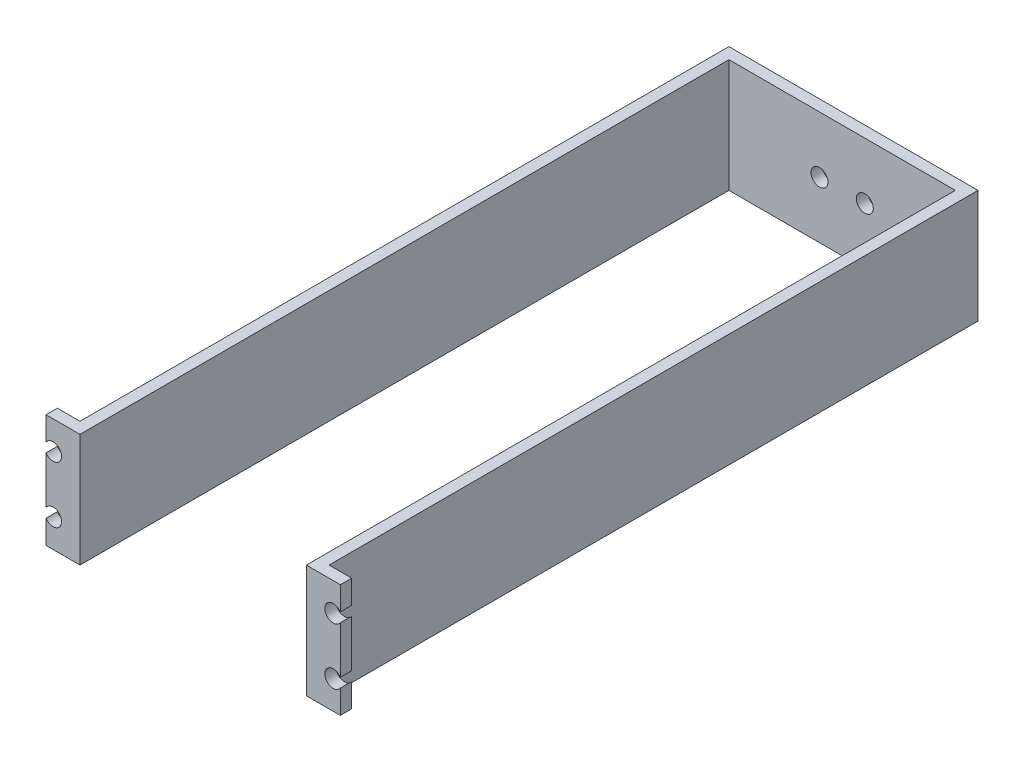
SolidWorks part; units mm, degrees
ref_plane "Plan de face" through (0, 0, 0) normal (0, 0, 1) x (1, 0, 0)
ref_plane "Plan de dessus" through (0, 0, 0) normal (0, 1, 0) x (1, 0, 0)
ref_plane "Plan de droite" through (0, 0, 0) normal (1, 0, 0) x (0, 0, -1)
sketch "Esquisse1" plane through (0, 0, 0) normal (0, 0, 1) x (1, 0, 0)
  line L1 (0, 0) -> (44, 0)
  line L2 (0, 0) -> (0, 20)
  line L3 (0, 20) -> (44, 20)
  line L4 (44, 0) -> (44, 20)
  dimension "D1" = 20
  dimension "D2" = 44
extrude "Boss.-Extru.1" add sketch "Esquisse1" along normal blind 2
sketch "Esquisse2" plane through (0, 0, 2) normal (0, 0, 1) x (1, 0, 0)
  line L0 (0, 0) -> (44, 0) construction
  line L1 (0, 20) -> (2, 20)
  line L2 (0, 20) -> (0, 0)
  line L3 (0, 0) -> (2, 0)
  line L4 (2, 20) -> (2, 0)
  line L6 (44, 20) -> (42, 20)
  line L7 (44, 20) -> (44, 0)
  line L8 (44, 0) -> (42, 0)
  line L9 (42, 20) -> (42, 0)
  dimension "D1" = 2
  dimension "D2" = 2
extrude "Boss.-Extru.2" add sketch "Esquisse2" along normal blind 114.65
sketch "Esquisse3" plane through (0, 0, 0) normal (-1, 0, 0) x (0, 0, 1)
  line L0 (116.65, 0) -> (0, 0) construction
  line L1 (116.65, 20) -> (114.65, 20)
  line L2 (116.65, 20) -> (116.65, 0)
  line L3 (116.65, 0) -> (114.65, 0)
  line L4 (114.65, 20) -> (114.65, 0)
  dimension "D1" = 2
extrude "Boss.-Extru.3" add sketch "Esquisse3" along normal blind 4
sketch "Esquisse4" plane through (44, 0, 0) normal (1, 0, 0) x (0, 0, -1)
  line L0 (-116.65, 0) -> (0, 0) construction
  line L1 (-116.65, 20) -> (-114.65, 20)
  line L2 (-116.65, 20) -> (-116.65, 0)
  line L3 (-116.65, 0) -> (-114.65, 0)
  line L4 (-114.65, 20) -> (-114.65, 0)
  dimension "D1" = 2
extrude "Boss.-Extru.4" add sketch "Esquisse4" along normal blind 4
sketch "Esquisse5" plane through (0, 0, 2) normal (0, 0, 1) x (1, 0, 0)
  line L0 (42, 20) -> (2, 20) construction
  line L1 (2, 0) -> (2, 20) construction
  line L2 (42, 20) -> (42, 0) construction
  circle A0 centre (18, 10) radius 1.5
  circle A1 centre (26, 10) radius 1.5
  dimension "D5" = 3
  dimension "D6" = 3
  dimension "D1" = 10
  dimension "D2" = 16
  dimension "D3" = 10
  dimension "D4" = 16
extrude "Enlèv. mat.-Extru.1" cut sketch "Esquisse5" against normal blind 4
sketch "Esquisse6" plane through (0, 0, 116.65) normal (0, 0, 1) x (1, 0, 0)
  line L0 (2, 0) -> (2, 20) construction
  line L1 (42, 20) -> (42, 0) construction
  line L2 (48, 20) -> (42, 20) construction
  line L3 (42, 0) -> (48, 0) construction
  line L4 (2, 20) -> (-4, 20) construction
  line L5 (-4, 0) -> (2, 0) construction
  circle A0 centre (46.75, 15) radius 1.5
  circle A1 centre (46.75, 5) radius 1.5
  circle A2 centre (-2.75, 15) radius 1.5
  circle A3 centre (-2.75, 5) radius 1.5
  dimension "D1" = 3
  dimension "D2" = 3
  dimension "D3" = 3
  dimension "D4" = 3
  dimension "D5" = 4.75
  dimension "D6" = 4.75
  dimension "D7" = 4.75
  dimension "D8" = 4.75
  dimension "D9" = 5
  dimension "D10" = 5
  dimension "D11" = 5
  dimension "D12" = 5
extrude "Enlèv. mat.-Extru.2" cut sketch "Esquisse6" against normal blind 4
